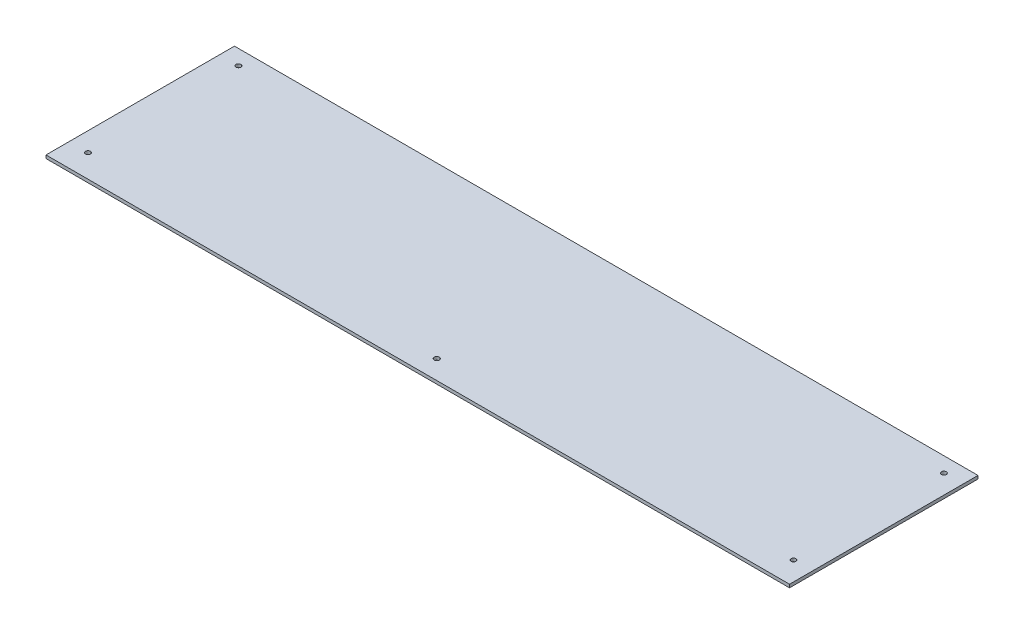
SolidWorks part; units mm, degrees
ref_plane "Alzado" through (0, 0, 0) normal (0, 0, 1) x (1, 0, 0)
ref_plane "Planta" through (0, 0, 0) normal (0, 1, 0) x (1, 0, 0)
ref_plane "Vista lateral" through (0, 0, 0) normal (1, 0, 0) x (0, 0, -1)
sketch "Croquis1" plane through (0, 0, 0) normal (0, 1, 0) x (1, 0, 0)
  line L0 (235.25, 120) -> (235.25, 0) construction
  line L1 (0, 0) -> (470.5, 0)
  line L2 (0, 0) -> (0, 120)
  line L3 (0, 120) -> (470.5, 120)
  line L4 (470.5, 0) -> (470.5, 120)
  line L5 (0, 60) -> (470.5, 60) construction
  circle A0 centre (12.5, 15) radius 1.55
  circle A1 centre (12.5, 110) radius 1.55
  circle A2 centre (458, 15) radius 1.55
  circle A3 centre (458, 110) radius 1.55
  dimension "D3" = 3.1
  dimension "D1" = 120
  dimension "D2" = 470.5
  dimension "D4" = 15
  dimension "D5" = 12.5
  dimension "D6" = 12.5
  dimension "D7" = 10
extrude "Saliente-Extruir1" add sketch "Croquis1" along normal blind 2
sketch "Croquis2" plane through (0, 0, 0) normal (0, -1, 0) x (1, 0, 0)
  line L0 (470, -0.5) -> (0.5, -0.5)
  line L1 (0.5, -0.5) -> (0.5, -119.5)
  line L2 (0.5, -119.5) -> (470, -119.5)
  line L3 (470, -119.5) -> (470, -0.5)
  line L4 (0, 0) -> (0, -120)
  line L5 (0, -120) -> (470.5, -120)
  line L6 (470.5, -120) -> (470.5, 0)
  line L7 (470.5, 0) -> (0, 0)
  line L8 (0, 0) -> (0, -120)
  line L9 (0, -120) -> (470.5, -120)
  line L10 (470.5, -120) -> (470.5, 0)
  line L11 (470.5, 0) -> (0, 0)
  dimension "D1" = 0
  dimension "D2" = 0.5
extrude "Cortar-Extruir1" cut sketch "Croquis2" against normal up to surface (2 mm away) up to face at (235.25, 2, -60)
sketch "Croquis3" plane through (0, 0, 0) normal (0, -1, 0) x (1, 0, 0)
  line L0 (235.25, -0.5) -> (235.25, -119.5) construction
  line L1 (470, -0.5) -> (0.5, -0.5) construction
  line L2 (0.5, -119.5) -> (470, -119.5) construction
  circle A0 centre (235.25, -12.5) radius 1.6
  dimension "D1" = 3.2
  dimension "D2" = 12
extrude "Cortar-Extruir2" cut sketch "Croquis3" against normal up to surface (2 mm away) up to face at (458, 2, -111.55)
